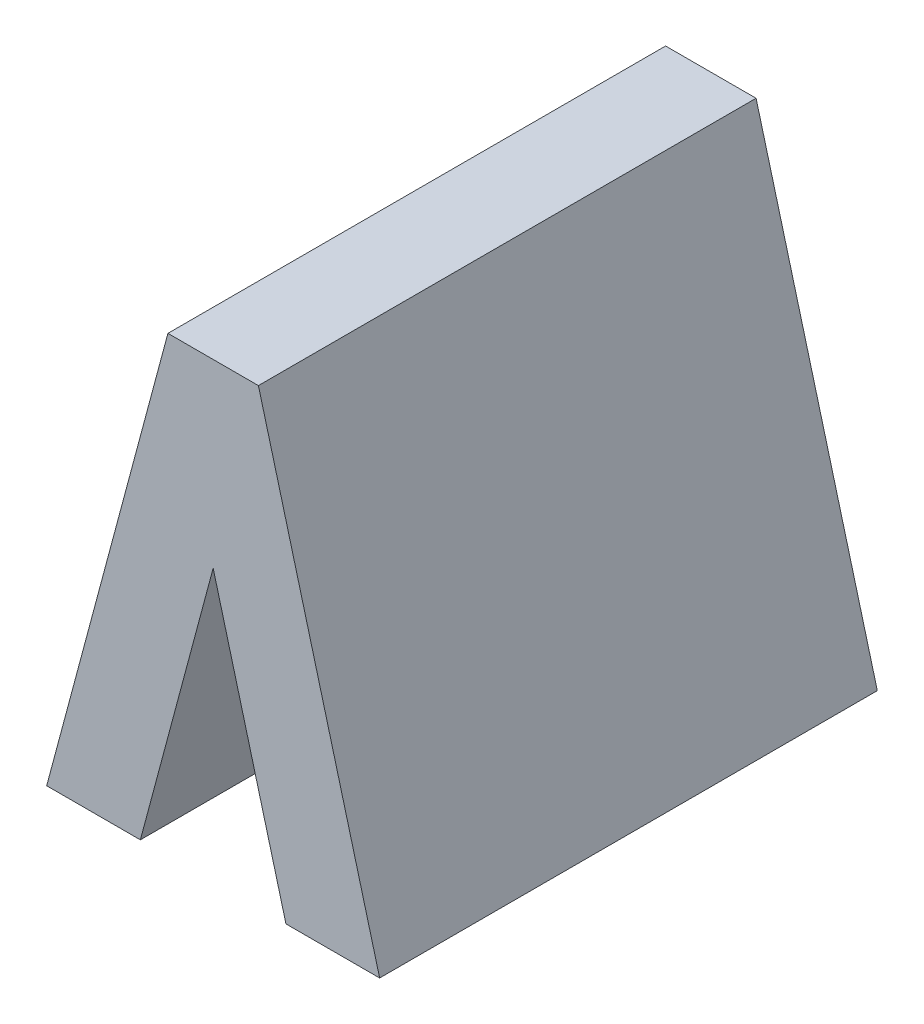
SolidWorks part; units mm, degrees
ref_plane "Alzado" through (0, 0, 0) normal (0, 0, 1) x (1, 0, 0)
ref_plane "Planta" through (0, 0, 0) normal (0, 1, 0) x (1, 0, 0)
ref_plane "Vista lateral" through (0, 0, 0) normal (1, 0, 0) x (0, 0, -1)
sketch "Croquis1" plane through (0, 0, 0) normal (0, 0, 1) x (1, 0, 0)
  line L1 (-0.3736, 0) -> (-27.1686, -100)
  line L5 (9.6264, -39.9536) -> (-6.463, -100)
  line L6 (-6.463, -100) -> (-27.1686, -100)
  line L8 (-0.3736, 0) -> (19.6264, 0)
  line L10 (9.6264, 1031.2095) -> (9.6264, 0) construction
  line L14 (25.7158, -100) -> (46.4213, -100)
  line L15 (9.6264, -39.9536) -> (25.7158, -100)
  line L16 (19.6264, 0) -> (46.4213, -100)
  line L17 (9.6264, -39.9536) -> (9.6264, -50031.2095) construction
  point P5 (-3.9847, 0)
  point P9 (-116.6335, -57.4772)
  point P13 (6.7701, 19.1864)
  dimension "D1" = 20
  dimension "D4" = 20
extrude "Saliente-Extruir1" add sketch "Croquis1" along normal blind 110
